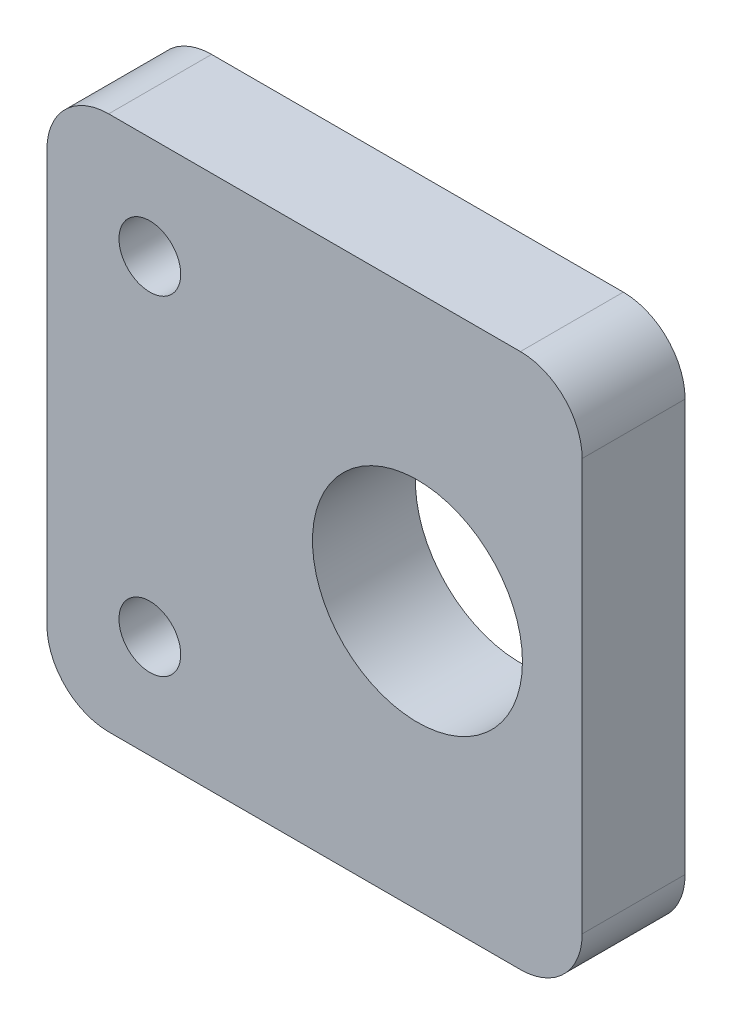
SolidWorks part; units mm, degrees
ref_plane "Alzado" through (0, 0, 0) normal (0, 0, 1) x (1, 0, 0)
ref_plane "Planta" through (0, 0, 0) normal (0, 1, 0) x (1, 0, 0)
ref_plane "Vista lateral" through (0, 0, 0) normal (1, 0, 0) x (0, 0, -1)
sketch "Croquis1" plane through (0, 0, 0) normal (0, 0, 1) x (1, 0, 0)
  line L0 (0, 0) -> (-20.2413, 0) construction
  line L1 (-9, -9.5435) -> (-9, 10.5966) construction
  line L6 (-18, 13) -> (8, -13) construction
  line L7 (-18, -13) -> (8, -13)
  line L8 (-18, -13) -> (-18, 13)
  line L9 (-18, 13) -> (8, 13)
  line L10 (8, -13) -> (8, 13)
  circle A0 centre (0, 0) radius 5.1
  circle A3 centre (-13, 8) radius 1.5
  circle A5 centre (-13, -8) radius 1.5
  point P12 (-5, 0)
  dimension "D1" = 10.2
  dimension "D2" = 13
  dimension "D3" = 8
  dimension "D5" = 3
  dimension "D4" = 8
  dimension "D6" = 5
  dimension "D7" = 5
extrude "Saliente-Extruir1" add sketch "Croquis1" along normal blind 5
fillet "Redondeo1" radius 3 4 edges at (-18, -13, 2.5) (-18, 13, 2.5) (8, -13, 2.5) (8, 13, 2.5)
